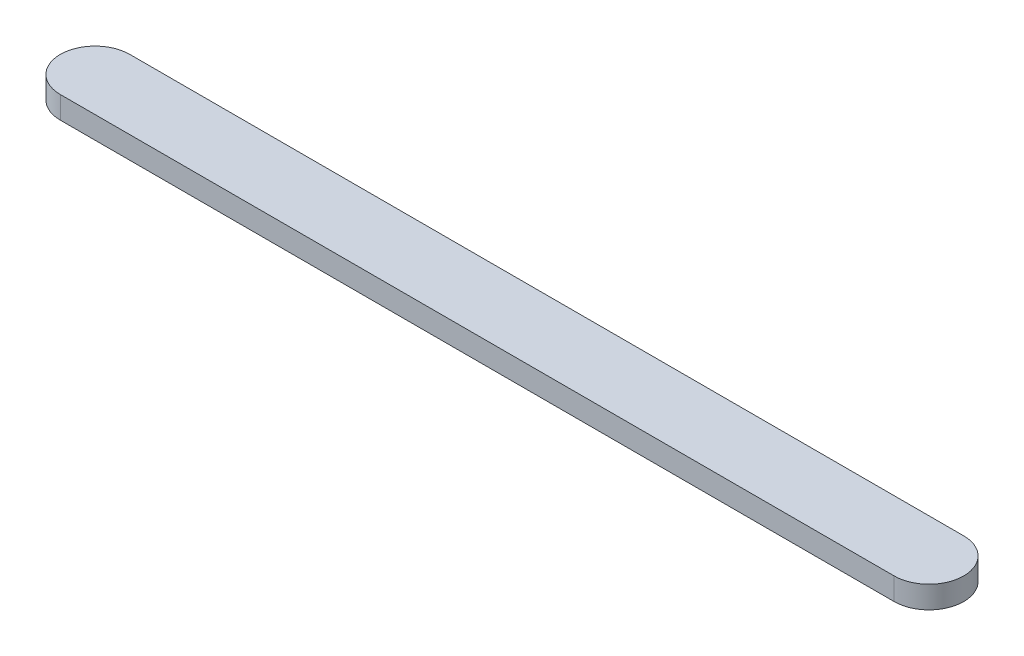
SolidWorks part; units mm, degrees
ref_plane "Front Plane" through (0, 0, 0) normal (0, 0, 1) x (1, 0, 0)
ref_plane "Top Plane" through (0, 0, 0) normal (0, 1, 0) x (1, 0, 0)
ref_plane "Right Plane" through (0, 0, 0) normal (1, 0, 0) x (0, 0, -1)
sketch "Sketch2" plane through (0, 0, 0) normal (0, 1, 0) x (1, 0, 0)
  line L0 (-39.6792, 0) -> (36.5208, 0) construction
  line L1 (-39.6792, 3.175) -> (36.5208, 3.175)
  line L2 (-39.6792, -3.175) -> (36.5208, -3.175)
  arc A0 (-39.6792, 3.175) -> (-39.6792, -3.175) centre (-39.6792, 0) ccw
  arc A1 (36.5208, -3.175) -> (36.5208, 3.175) centre (36.5208, 0) ccw
  point P3 (-1.5792, 0)
  dimension "D1" = 76.2
  dimension "D2" = 76.2
  dimension "D3" = 76.2
  dimension "D4" = 6.35
extrude "Boss-Extrude1" add sketch "Sketch2" along normal blind 2.032
